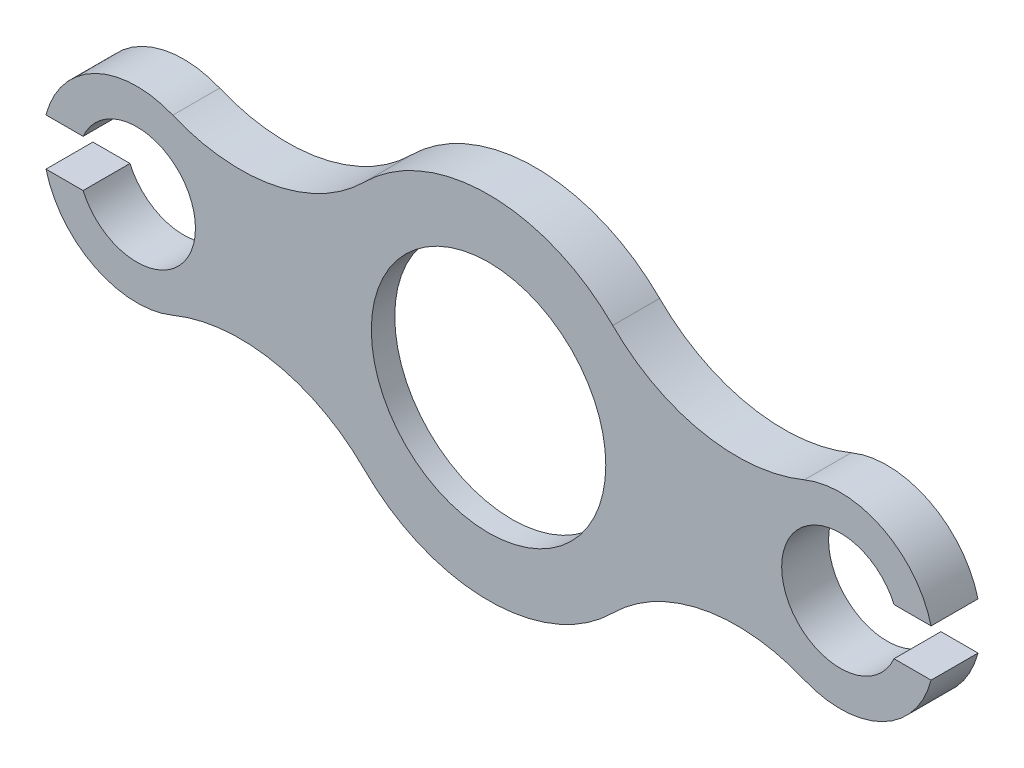
SolidWorks part; units mm, degrees
ref_plane "Front Plane" through (0, 0, 0) normal (0, 0, 1) x (1, 0, 0)
ref_plane "Top Plane" through (0, 0, 0) normal (0, 1, 0) x (1, 0, 0)
ref_plane "Right Plane" through (0, 0, 0) normal (1, 0, 0) x (0, 0, -1)
sketch "Sketch3" plane through (0, 0, 0) normal (0, 0, 1) x (1, 0, 0)
  line L0 (0, 0) -> (0, -128.2041) construction
  line L1 (0, 0) -> (102.7166, 0) construction
  line L2 (188.7298, 10) -> (172.9129, 10)
  line L4 (172.9129, -10) -> (188.7298, -10)
  line L6 (0, 0) -> (-102.7166, 0) construction
  line L7 (-172.9129, -10) -> (-188.7298, -10)
  line L8 (-188.7298, 10) -> (-172.9129, 10)
  arc A0 (52.9583, 53.1076) -> (-52.9583, 53.1076) centre (0, 0) ccw
  arc A1 (188.7298, 10) -> (188.7298, -10) centre (150, 0) ccw
  arc A2 (172.9129, 10) -> (172.9129, -10) centre (150, 0) ccw
  arc A3 (52.9583, 53.1076) -> (134.6667, 36.9444) centre (105.9167, 106.2152) ccw
  arc A4 (52.9583, -53.1076) -> (134.6667, -36.9444) centre (105.9167, -106.2152) cw
  arc A7 (-52.9583, -53.1076) -> (-134.6667, -36.9444) centre (-105.9167, -106.2152) ccw
  arc A8 (-52.9583, 53.1076) -> (-134.6667, 36.9444) centre (-105.9167, 106.2152) cw
  arc A9 (-172.9129, 10) -> (-172.9129, -10) centre (-150, 0) cw
  arc A10 (-188.7298, 10) -> (-188.7298, -10) centre (-150, 0) cw
  arc A11 (-52.9583, -53.1076) -> (52.9583, -53.1076) centre (0, 0) ccw
  point P32 (0, 0)
  point P33 (0, 0)
  dimension "D1" = 150
  dimension "D2" = 80
  dimension "D3" = 50
  dimension "D9" = 75
  dimension "D4" = 150
  dimension "D7" = 20
  dimension "D8" = 15.817
extrude "Boss-Extrude8" add sketch "Sketch3" along normal blind 20 contours A7 A11 A4 A1 A3 A0 A8 A10 | A10 L8 A9 L7 | A2 L2 A1 L4
sketch "Sketch5" plane through (0, 0, 20) normal (0, 0, 1) x (1, 0, 0)
  circle A0 centre (0, 0) radius 50
  dimension "D1" = 100
extrude "Cut-Extrude1" cut sketch "Sketch5" against normal blind 10
sketch "Sketch7" plane through (0, 0, 0) normal (0, 0, -1) x (-1, 0, 0)
  circle A0 centre (0, 0) radius 67.8
  dimension "D1" = 135.6
extrude "Cut-Extrude3" cut sketch "Sketch7" against normal blind 10
